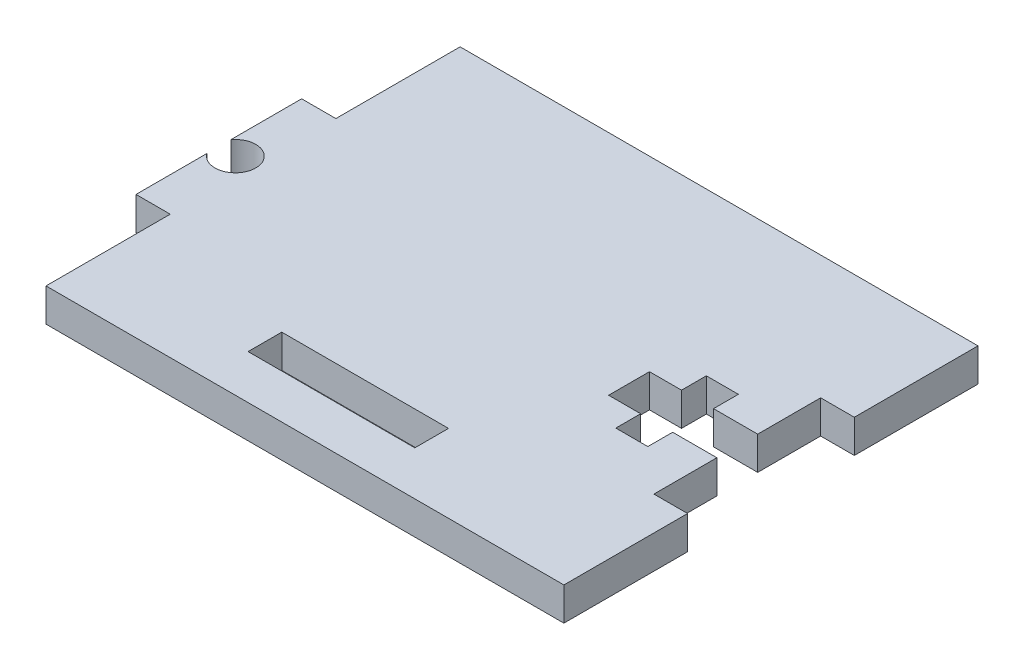
SolidWorks part; units mm, degrees
ref_plane "Front" through (0, 0, 0) normal (0, 0, 1) x (1, 0, 0)
ref_plane "Top" through (0, 0, 0) normal (0, 1, 0) x (1, 0, 0)
ref_plane "Right" through (0, 0, 0) normal (1, 0, 0) x (0, 0, -1)
sketch "Sketch1" plane through (0, 0, 0) normal (0, 1, 0) x (1, 0, 0)
  line L1 (-25, 18.75) -> (25, 18.75)
  line L2 (-25, 18.75) -> (-25, -18.75)
  line L3 (-25, -18.75) -> (25, -18.75)
  line L4 (25, 18.75) -> (25, -18.75)
  line L5 (-25, 18.75) -> (25, -18.75) construction
  line L6 (-25, -18.75) -> (25, 18.75) construction
  point P0 (0, 0)
  dimension "D1" = 37.5
  dimension "D2" = 50
extrude "Boss-Extrude1" add sketch "Sketch1" along normal blind 3
sketch "Sketch2" plane through (0, 3, 0) normal (0, 1, 0) x (1, 0, 0)
  line L0 (-25, 18.75) -> (-25, -18.75) construction
  line L1 (-7.6, -11.7) -> (7.5, -11.7)
  line L2 (-7.6, -11.7) -> (-7.6, -14.75)
  line L3 (-7.6, -14.75) -> (7.5, -14.75)
  line L4 (7.5, -11.7) -> (7.5, -14.75)
  line L5 (-7.6, -11.7) -> (7.5, -14.75) construction
  line L6 (-7.6, -14.75) -> (7.5, -11.7) construction
  line L7 (-25, -18.75) -> (25, -18.75) construction
  point P0 (-0.05, -13.225)
  dimension "D1" = 3.05
  dimension "D2" = 15.1
  dimension "D3" = 17.4
  dimension "D4" = 4
extrude "Cut-Extrude1" cut sketch "Sketch2" against normal through all
sketch "Sketch3" plane through (0, 3, 0) normal (0, 1, 0) x (1, 0, 0)
  line L0 (25, 7.55) -> (21.95, 7.55)
  line L1 (25, -18.75) -> (25, 18.75) construction
  line L2 (21.95, 7.55) -> (21.95, 1.85)
  line L3 (21.95, 1.85) -> (17.95, 1.85)
  line L4 (17.95, 1.85) -> (17.95, 4.1)
  line L5 (17.95, 4.1) -> (15.05, 4.1)
  line L6 (15.05, 4.1) -> (15.05, 1.85)
  line L7 (15.05, 1.85) -> (12.15, 1.85)
  line L8 (12.15, 1.85) -> (12.15, 0)
  line L9 (12.15, 0) -> (25, 0)
  line L10 (25, 0) -> (25, 7.55)
  dimension "D1" = 3.05
  dimension "D2" = 7.55
  dimension "D3" = 4.1
  dimension "D4" = 2.9
  dimension "D5" = 4
  dimension "D6" = 9.8
  dimension "D7" = 1.85
extrude "Cut-Extrude2" cut sketch "Sketch3" against normal through all
mirror "Mirror1" about plane through (0, 0, 0) normal (0, 0, 1) of "Cut-Extrude2"
sketch "Sketch4" plane through (0, 0, 0) normal (0, -1, 0) x (1, 0, 0)
  line L1 (-25, -18.75) -> (-21.9, -18.75)
  line L2 (-25, -18.75) -> (-25, -7.5)
  line L3 (-25, -7.5) -> (-21.9, -7.5)
  line L4 (-21.9, -18.75) -> (-21.9, -7.5)
  line L5 (-25, 18.75) -> (-21.9, 18.75)
  line L6 (-25, 18.75) -> (-25, 7.5)
  line L7 (-25, 7.5) -> (-21.9, 7.5)
  line L8 (-21.9, 18.75) -> (-21.9, 7.5)
  dimension "D1" = 3.1
  dimension "D2" = 15
extrude "Cut-Extrude3" cut sketch "Sketch4" against normal through all
sketch "Sketch5" plane through (0, 0, 0) normal (0, -1, 0) x (1, 0, 0)
  line L0 (-23.5, 0) -> (0, 0) construction
  line L1 (-25, -7.5) -> (-25, 7.5) construction
  circle A0 centre (-23.5, 0) radius 1.85
  dimension "D2" = 3.7
  dimension "D1" = 1.5
extrude "Cut-Extrude4" cut sketch "Sketch5" against normal through all
